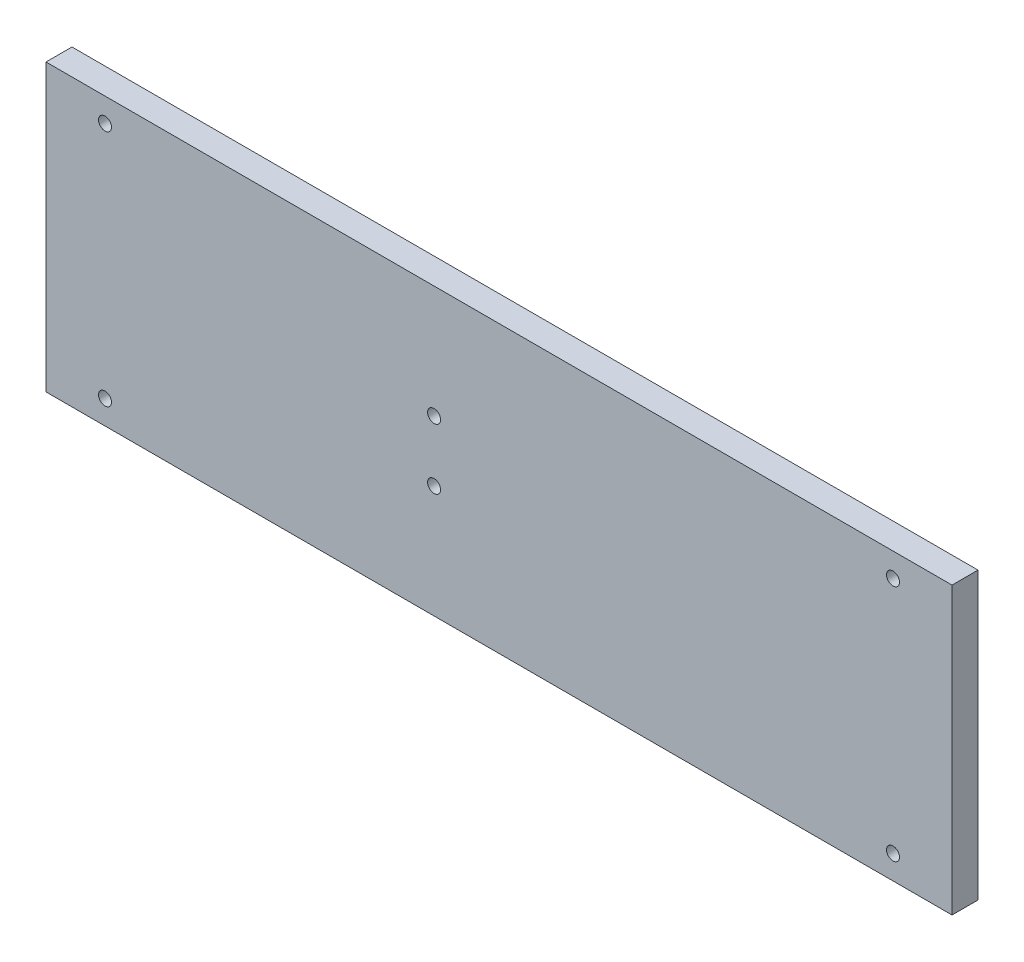
SolidWorks part; units mm, degrees
ref_plane "Plan de face" through (0, 0, 0) normal (0, 0, 1) x (1, 0, 0)
ref_plane "Plan de dessus" through (0, 0, 0) normal (0, 1, 0) x (1, 0, 0)
ref_plane "Plan de droite" through (0, 0, 0) normal (1, 0, 0) x (0, 0, -1)
sketch "Esquisse1" plane through (0, 0, 0) normal (0, 0, 1) x (1, 0, 0)
  line L1 (-104.63, 33) -> (104.63, 33)
  line L2 (-104.63, 33) -> (-104.63, -33)
  line L3 (-104.63, -33) -> (104.63, -33)
  line L4 (104.63, 33) -> (104.63, -33)
  dimension "D1" = 209.26
  dimension "D2" = 66
  dimension "D3" = 104.63
  dimension "D4" = 33
extrude "Boss.-Extru.1" add sketch "Esquisse1" along normal blind 6
sketch "Esquisse2" plane through (0, 0, 6) normal (0, 0, 1) x (1, 0, 0)
  line L0 (0, 49.0616) -> (0, -42.9956) construction
  line L2 (-104.63, -33) -> (104.63, -33) construction
  line L3 (91, 32.7086) -> (91, -49.0227) construction
  line L6 (-91, 32.7086) -> (-91, -49.0227) construction
  line L7 (104.63, -33) -> (104.63, 33) construction
  circle A8 centre (-15, 7) radius 1.5
  circle A9 centre (-15, -7) radius 1.5
  circle A10 centre (91, 27.5) radius 1.5
  circle A11 centre (91, -27.5) radius 1.5
  circle A12 centre (-91, -27.5) radius 1.5
  circle A13 centre (-91, 27.5) radius 1.5
  dimension "D12" = 3
  dimension "D14" = 3
  dimension "D13" = 26
  dimension "D15" = 15
  dimension "D19" = 3
  dimension "D20" = 3
  dimension "D21" = 55
  dimension "D22" = 5.5
  dimension "D16" = 14
  dimension "D17" = 15
  dimension "D23" = 13.63
extrude "Enlèv. mat.-Extru.1" cut sketch "Esquisse2" against normal blind 6
equation "\"D3@Esquisse1\"=\"D1@Esquisse1\"/2"
equation "\"D4@Esquisse1\"=\"D2@Esquisse1\"/2"
